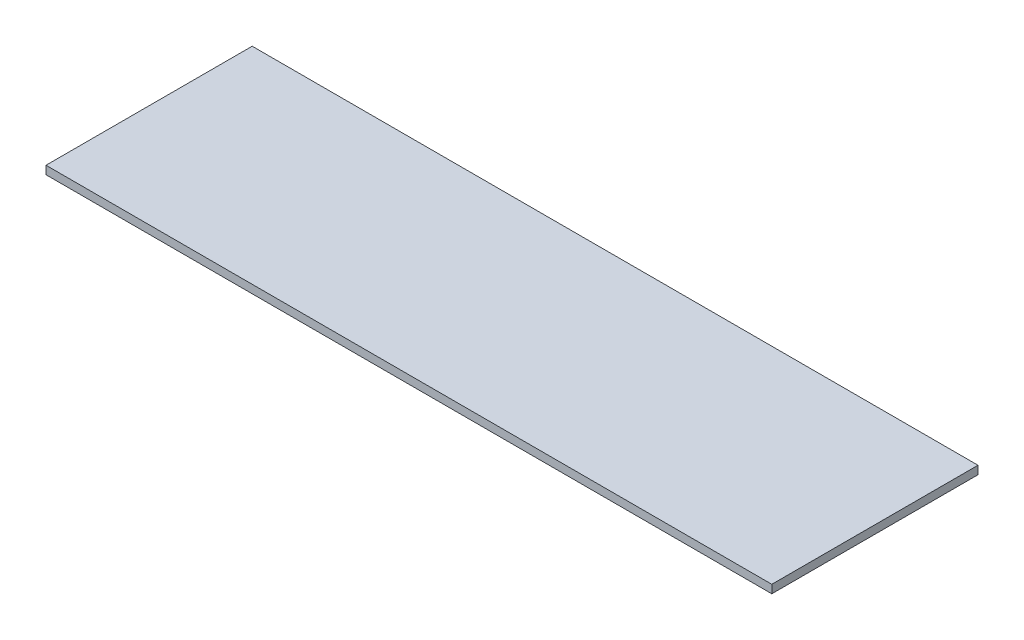
SolidWorks part; units mm, degrees
material "ABS"
ref_plane "Front Plane" through (0, 0, 0) normal (0, 0, 1) x (1, 0, 0)
ref_plane "Top Plane" through (0, 0, 0) normal (0, 1, 0) x (1, 0, 0)
ref_plane "Right Plane" through (0, 0, 0) normal (1, 0, 0) x (0, 0, -1)
sketch "Sketch1" plane through (0, 0, 0) normal (0, 1, 0) x (1, 0, 0)
  line L1 (88, 25) -> (-88, 25)
  line L2 (88, 25) -> (88, -25)
  line L3 (88, -25) -> (-88, -25)
  line L4 (-88, 25) -> (-88, -25)
  line L5 (88, 25) -> (-88, -25) construction
  line L6 (88, -25) -> (-88, 25) construction
  point P0 (0, 0)
  point P17 (-77.3938, -9.6502)
  point P18 (0, 0)
  point P19 (-52.9741, -9.6306)
  dimension "D1" = 176
  dimension "D2" = 50
extrude "Boss-Extrude1" add sketch "Sketch1" along normal blind 2
